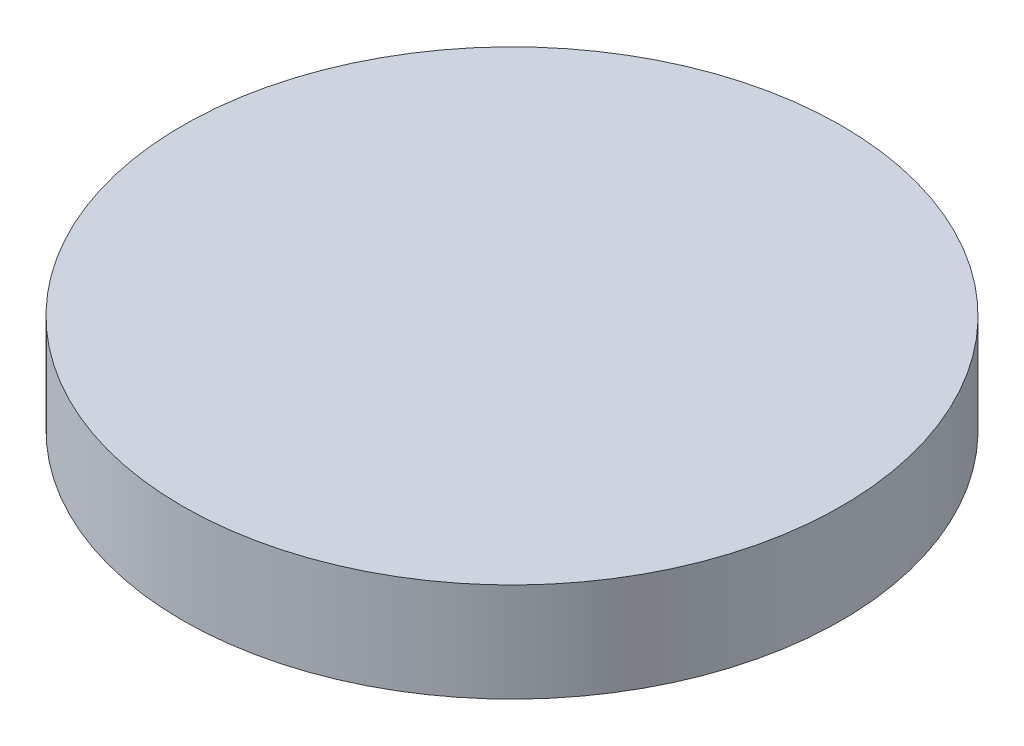
SolidWorks part; units mm, degrees
ref_plane "Front Plane" through (0, 0, 0) normal (0, 0, 1) x (1, 0, 0)
ref_plane "Top Plane" through (0, 0, 0) normal (0, 1, 0) x (1, 0, 0)
ref_plane "Right Plane" through (0, 0, 0) normal (1, 0, 0) x (0, 0, -1)
sketch "Sketch1" plane through (0, 0, 0) normal (0, 1, 0) x (1, 0, 0)
  circle A0 centre (0, 0) radius 63.5
  dimension "D1" = 127
extrude "Boss-Extrude1" add sketch "Sketch1" along normal blind 19.05
